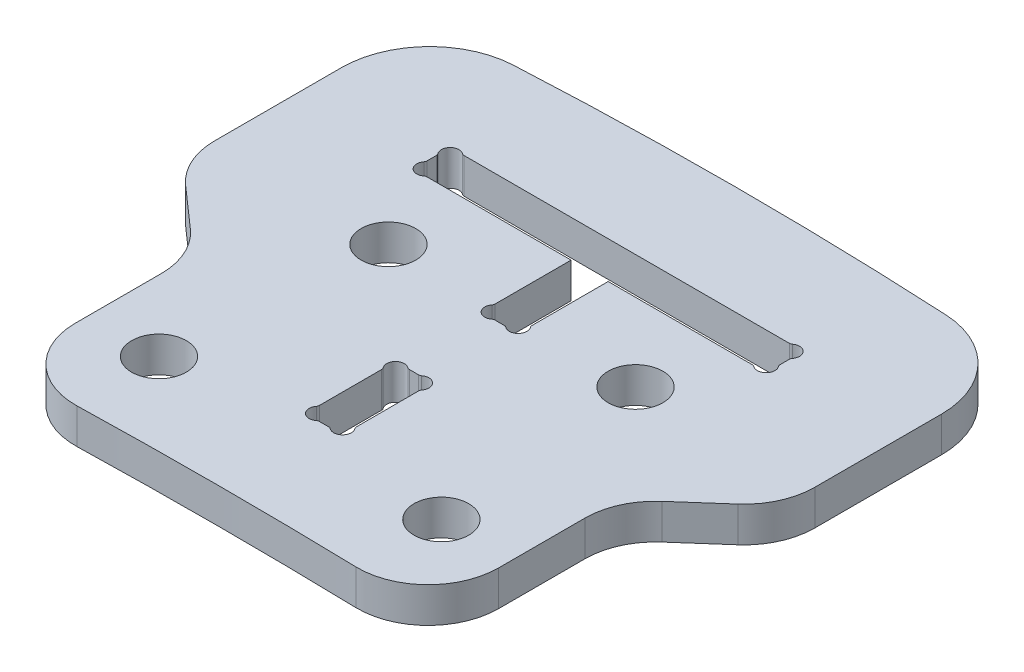
SolidWorks part; units mm, degrees
ref_plane "前视基准面" through (0, 0, 0) normal (0, 0, 1) x (1, 0, 0)
ref_plane "上视基准面" through (0, 0, 0) normal (0, 1, 0) x (1, 0, 0)
ref_plane "右视基准面" through (0, 0, 0) normal (1, 0, 0) x (0, 0, -1)
other "Configuration Table"
sketch "草图1" plane through (0, 0, 0) normal (0, 1, 0) x (1, 0, 0)
  line L0 (0, 0) -> (0, 106.8)
  line L1 (0, 106.8) -> (0, 341.8)
  line L2 (12, 341.4934) -> (12, 0)
  line L3 (12, 0) -> (0, 0)
  line L4 (-12, 341.4934) -> (-12, 0)
  line L5 (-12, 0) -> (0, 0)
  line L6 (0, 312.5) -> (17, 327.5)
  line L7 (17, 327.5) -> (17, 341.1843)
  line L8 (0, 312.5) -> (-17, 327.5)
  line L9 (-17, 327.5) -> (-17, 341.1843)
  line L10 (17, 327.5) -> (-17, 327.5)
  circle A0 centre (0, 0) radius 312.5
  circle A1 centre (0, 106.8) radius 235
  dimension "D1" = 625
  dimension "D3" = 470
  dimension "D2" = 106.8
  dimension "D4" = 12
  dimension "D5" = 12
  dimension "D6" = 5
  dimension "D7" = 5
  dimension "D8" = 15
extrude "凸台-拉伸1" add sketch "草图1" along normal blind 2 contours L2 A1 L1 A0 | L1 A1 L4 A0 | L2 L10 L1 L6 | L1 L10 L4 L8 | A0 L8 L4 | L4 L10 L8 | L4 A1 L9 L10 | L7 A1 L2 L10 | L6 L10 L2 | A0 L2 L6
sketch "草图2" plane through (0, 2, 0) normal (0, 1, 0) x (1, 0, 0)
  line L0 (0, 312.5) -> (0, 341.8) construction
  line L1 (-1.05, 318.5) -> (1.05, 318.5)
  line L2 (1.05, 318.5) -> (1.05, 323.6)
  line L3 (1.05, 323.6) -> (-1.05, 323.6)
  line L4 (0, 323.6) -> (0, 328.45)
  line L5 (-1.05, 328.45) -> (1.05, 328.45)
  line L6 (1.05, 328.45) -> (1.05, 333.55)
  line L7 (1.05, 333.55) -> (10, 333.55)
  line L8 (10, 333.55) -> (10, 335.65)
  line L9 (10, 335.65) -> (-10, 335.65)
  line L10 (-1.05, 318.5) -> (-1.05, 323.6)
  line L11 (-1.05, 328.45) -> (-1.05, 333.55)
  line L12 (-1.05, 333.55) -> (-10, 333.55)
  line L13 (-10, 333.55) -> (-10, 335.65)
  arc A0 (12, 312.2695) -> (-12, 312.2695) centre (0, 0) ccw construction
  arc A1 (17, 341.1843) -> (-17, 341.1843) centre (0, 106.8) ccw construction
  point P21 (0, 318.5)
  point P26 (0, 335.65)
  dimension "D6" = 318.5
  dimension "D1" = 2.1
  dimension "D2" = 10
  dimension "D3" = 5.1
  dimension "D4" = 5.1
  dimension "D5" = 4.85
  dimension "D7" = 1.05
extrude "切除-拉伸1" cut sketch "草图2" against normal through all contours L0 L5 L6 L7 L8 L9 | L5 L0 L9 L13 L12 L11 | L0 L1 L2 L3 | L1 L0 L3 L10
sketch "草图3" plane through (0, 2, 0) normal (0, 1, 0) x (1, 0, 0)
  line L0 (10, 334.9429) -> (9.2929, 335.65)
  line L1 (10, 333.55) -> (10, 335.65) construction
  line L2 (10, 335.65) -> (-10, 335.65) construction
  line L3 (10, 334.2571) -> (9.2929, 333.55)
  line L4 (1.05, 333.55) -> (10, 333.55) construction
  line L5 (1.05, 329.1571) -> (0.3429, 328.45)
  line L6 (-1.05, 328.45) -> (1.05, 328.45) construction
  line L7 (1.05, 328.45) -> (1.05, 333.55) construction
  line L8 (0.3429, 323.6) -> (1.05, 322.8929)
  line L9 (1.05, 318.5) -> (1.05, 323.6) construction
  line L10 (1.05, 319.2071) -> (0.3429, 318.5)
  line L11 (-1.05, 318.5) -> (1.05, 318.5) construction
  line L12 (0.6964, 323.2464) -> (1.05, 323.6)
  line L13 (0.6964, 318.8536) -> (1.05, 318.5)
  line L14 (1.05, 323.6) -> (-1.05, 323.6) construction
  line L15 (0.6964, 328.8036) -> (1.05, 328.45)
  line L16 (9.6464, 333.9036) -> (10, 333.55)
  line L17 (9.6464, 335.2964) -> (10, 335.65)
  circle A0 centre (9.6464, 333.9036) radius 0.5
  circle A1 centre (9.6464, 335.2964) radius 0.5
  circle A2 centre (0.6964, 328.8036) radius 0.5
  circle A3 centre (0.6964, 323.2464) radius 0.5
  circle A4 centre (0.6964, 318.8536) radius 0.5
  line M11 (-10, 335.65) -> (10, 335.65)
  line M12 (10, 335.65) -> (10, 333.55)
  line M13 (10, 333.55) -> (1.05, 333.55)
  line M14 (1.05, 333.55) -> (1.05, 328.45)
  line M15 (1.05, 328.45) -> (-1.05, 328.45)
  line M19 (-1.05, 323.6) -> (1.05, 323.6)
  line M20 (1.05, 323.6) -> (1.05, 318.5)
  line M21 (1.05, 318.5) -> (-1.05, 318.5)
  dimension "D1" = 1
extrude "切除-拉伸2" cut sketch "草图3" against normal through all contours A1 M12 | A1 M11 | A0 M12 | A0 M13 | A2 M14 | A2 M15 | A3 M20 | A3 M19 | A4 M20 | A4 M21
mirror "镜向1" about plane through (0, 0, 0) normal (1, 0, 0) of "切除-拉伸2"
fillet "圆角1" radius 0.2 20 edges at (1.05, 1, -322.8929) (1.05, 1, -319.2071) (-0.3429, 1, -318.5) (0.3429, 1, -318.5) (-1.05, 1, -319.2071) (-1.05, 1, -322.8929) (-0.3429, 1, -323.6) (0.3429, 1, -323.6) (-1.05, 1, -329.1571) (-0.3429, 1, -328.45) (0.3429, 1, -328.45) (1.05, 1, -329.1571) (9.2929, 1, -335.65) (10, 1, -334.9429) (10, 1, -334.2571) (9.2929, 1, -333.55) (-9.2929, 1, -333.55) (-10, 1, -334.2571) (-10, 1, -334.9429) (-9.2929, 1, -335.65)
sketch "草图4" plane through (0, 2, 0) normal (0, 1, 0) x (1, 0, 0)
  line L0 (0, 312.5) -> (0, 341.8)
  line L1 (9.218, 335.65) -> (-9.218, 335.65) construction
  arc A0 (12, 312.2695) -> (-12, 312.2695) centre (0, 0) ccw construction
  arc A1 (17, 341.1843) -> (-17, 341.1843) centre (0, 106.8) ccw construction
  circle A2 centre (7, 329.15) radius 1.55
  circle A3 centre (8, 317.15) radius 1.55
  dimension "D5" = 3.1
  dimension "D1" = 7
  dimension "D2" = 6.5
  dimension "D3" = 8
  dimension "D4" = 12
extrude "切除-拉伸3" cut sketch "草图4" against normal through all contours A2 | A3
mirror "镜向2" about plane through (0, 0, 0) normal (1, 0, 0) of "切除-拉伸3"
fillet "圆角2" radius 5 2 edges at (17, 1, -341.1843) (-17, 1, -341.1843)
fillet "圆角3" radius 4 6 edges at (12, 1, -323.0882) (17, 1, -327.5) (12, 1, -312.2695) (-12, 1, -312.2695) (-12, 1, -323.0882) (-17, 1, -327.5)
